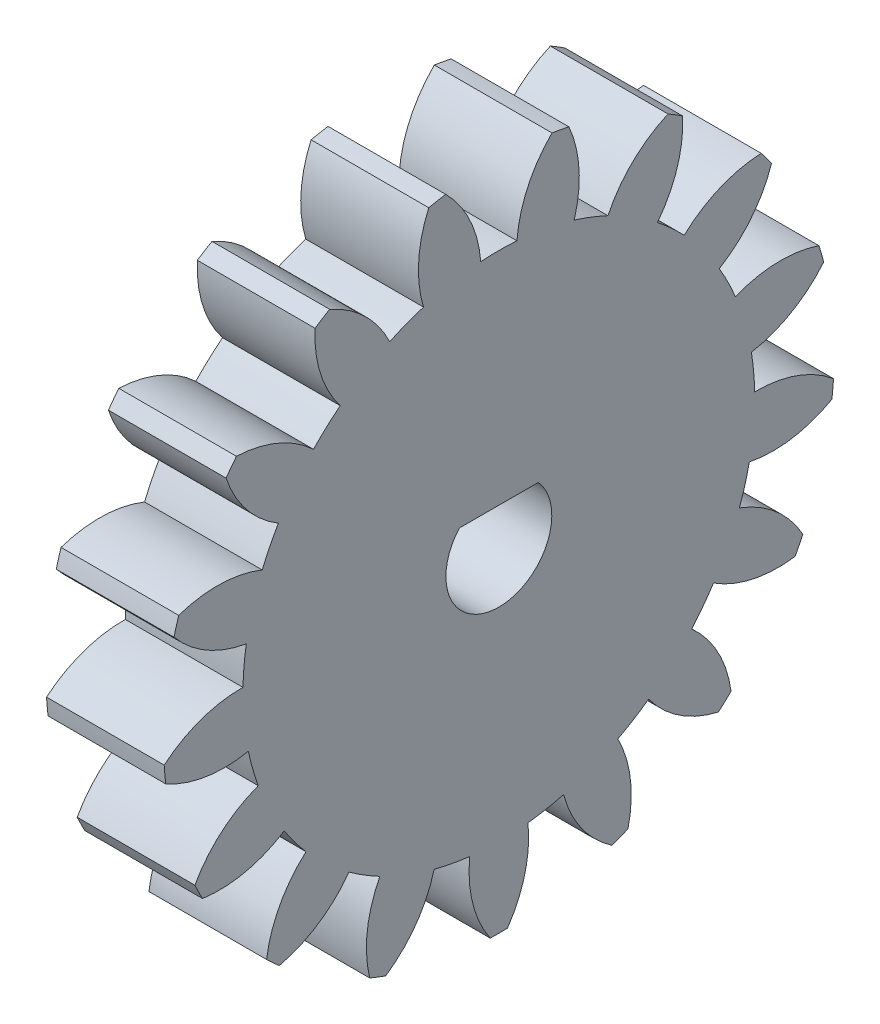
SolidWorks part; units mm, degrees
ref_plane "Plane1" through (0, 0, 0) normal (0, 0, 1) x (1, 0, 0)
ref_plane "Plane2" through (0, 0, 0) normal (0, 1, 0) x (1, 0, 0)
ref_plane "Plane3" through (0, 0, 0) normal (1, 0, 0) x (0, 0, -1)
sketch "HoldingSke" plane through (0, 0, 0) normal (0, 1, 0) x (1, 0, 0)
  line L0 (0, 0) -> (0.6375, -0.1949)
  line L1 (-15, 0) -> (100, 0) construction
  line L2 (0, 0) -> (-2.1039, 2.3779)
  line L3 (0, 0) -> (-11.863, 4.5341)
  line L4 (0, 0) -> (8.2586, 2.5249)
  line L5 (0, 0) -> (-46.8476, -17.4728)
  line L6 (0, 0) -> (-4.1448, -2.7965)
  line L7 (-2.1039, 2.3779) -> (8.6586, 51.2059)
  line L8 (-76.2, 54.61) -> (-76.1, 54.61)
  line L9 (-71.009, 38.7566) -> (-53.1078, 45.2721)
  line L10 (-76.2, 71.12) -> (104.1128, 71.12)
  line L11 (0, 0) -> (-5, 0)
  line L12 (-76.2, 101.6) -> (-76.147, 101.6)
  line L13 (24.9733, 27.94) -> (52.9518, 28.4284)
  line L14 (24.9733, 27.94) -> (24.9743, 27.94)
  line L15 (24.9733, 27.94) -> (100.4006, 29.5858)
  line L16 (-63.627, -1.5) -> (-12.827, -1.5)
  circle A0 centre (0, 0) radius 0.4
  circle A1 centre (0, 0) radius 10.874
  circle A2 centre (0, 0) radius 37.5
  circle A3 centre (0, 0) radius 0.4
  dimension "MHD" = 21.748
  dimension "Hub_dia" = 75
  dimension "Bore" = 0.8
  dimension "MBD" = 0.8
  dimension "Num_teeth" = 17
  dimension "Pitch" = 0.6667
  dimension "Overall_len" = 50
  dimension "Show_teeth" = 17
  dimension "Thickness" = 5
  dimension "OAL" = 50.0001
  dimension "T_dim" = 0.1
  dimension "Ap" = 20
  dimension "H" = 19.05
  dimension "Pitch_radius" = 180.3128
  dimension "Width" = 5
  dimension "Backlash" = 0.053
  dimension "Addendum_fac" = 1
  dimension "Dedendum_fac" = 1.25
  dimension "Clearance_fac" = 0.25
  dimension "Dedendum_add" = 0.001
  dimension "Module" = 1.5
sketch "BasProSke" plane through (0, 0, 0) normal (0, 1, 0) x (1, 0, 0)
  line L0 (-10, 0) -> (60, 0) construction
  line L1 (0, 0) -> (0, 14.25)
  line L2 (0, 0) -> (5, 0)
  line L3 (5, 0) -> (5, 14.25)
  line L4 (5, 14.25) -> (0, 14.25)
  dimension "Thickness" = 5
  dimension "Diameter" = 28.5
revolve "Base-Revolve" add sketch "BasProSke" angle 360 about L0
sketch "TooCutSke" plane through (0, 0, 0) normal (1, 0, 0) x (0, 0, -1)
  line L1 (0, 0) -> (0, 107) construction
  line L2 (0, 0) -> (-1.2691, 12.6867) construction
  line L3 (0, 0) -> (-4.6687, 24.9751) construction
  line L4 (-1.2691, 12.6867) -> (-2.3343, 12.4876) construction
  arc A0 (0.7694, 10.8467) -> (-0.7694, 10.8467) centre (0, 0) ccw
  arc A1 (2.2806, 14.0921) -> (-2.2806, 14.0921) centre (0, 0) ccw
  circle A2 centre (0, 0) radius 12.75 construction
  circle A3 centre (0, 0) radius 11.9811 construction
  arc A4 (-0.7694, 10.8467) -> (-2.2806, 14.0921) centre (-5.8542, 10.4535) ccw
  arc A5 (2.2806, 14.0921) -> (0.7694, 10.8467) centre (5.8542, 10.4535) ccw
  dimension "Root_dia" = 21.748
  dimension "Overcut_dia" = 28.5508
  dimension "Pitch_dia" = 25.5
  dimension "Base_dia" = 23.9622
  dimension "Flank_rad" = 5.1
  dimension "Half_ang" = 10.588
  dimension "Half_CT" = 1.0837
extrude "ToothCut" cut sketch "TooCutSke" along normal through all
fillet "Breaks" [suppressed] radius 0.03
fillet "RootFillets" [suppressed] radius 0.376
pattern_circular "TeethCuts" count 17 every 21.176 about axis through (-10, 0, 0) along (1, 0, 0) of "ToothCut", "RootFillets", "Breaks"
sketch "HubNeaOneSke" plane through (0, 0, 0) normal (-1, 0, 0) x (0, 0, 1)
  circle A0 centre (0, 0) radius 10.874
  dimension "Diameter" = 21.748
extrude "HubNearOne" [suppressed] add sketch "HubNeaOneSke" along normal blind 45.0001
sketch "HubNeaBotSke" plane through (0, 0, 0) normal (-1, 0, 0) x (0, 0, 1)
  circle A0 centre (0, 0) radius 10.874
  dimension "Diameter" = 21.748
extrude "HubNearBoth" [suppressed] add sketch "HubNeaBotSke" along normal blind 22.5
ref_plane "FarPln" through (5, 0, 0) normal (1, 0, 0) x (0, 0, -1)
sketch "HubFarSke" plane through (5, 0, 0) normal (1, 0, 0) x (0, 0, -1)
  circle A0 centre (0, 0) radius 10.874
  dimension "Diameter" = 21.748
extrude "HubFar" [suppressed] add sketch "HubFarSke" along normal blind 22.5
sketch "BorSke" plane through (0, 0, 0) normal (1, 0, 0) x (0, 0, -1)
  circle A0 centre (0, 0) radius 0.4
  dimension "Diameter" = 0.8
extrude "Bore" cut sketch "BorSke" along normal mid plane 100.0001
sketch "KeySke" plane through (0, 0, 0) normal (1, 0, 0) x (0, 0, -1)
  line L0 (-0.05, 0) -> (-0.05, 0.5)
  line L1 (-0.05, 0.5) -> (0.05, 0.5)
  line L2 (0.05, 0.5) -> (0.05, 0)
  line L3 (0, 0) -> (0, 34) construction
  line L4 (-0.05, 0) -> (0.05, 0)
  dimension "Offset" = 0.5
  dimension "Width" = 0.1
extrude "Keyway" [suppressed] cut sketch "KeySke" along normal mid plane 100.0001
pattern_circular "Keyway2" [suppressed] count 2 every 90 about axis through (-10, 0, 0) along (1, 0, 0)
sketch "Sketch1" plane through (5, 0, 0) normal (1, 0, 0) x (0, 0, -1)
  line L0 (-1.6771, 1.5) -> (1.6771, 1.5)
  arc A0 (-1.6771, 1.5) -> (1.6771, 1.5) centre (0, 0) ccw
  dimension "D1" = 2.25
  dimension "D2" = 1.5
extrude "Cut-Extrude1" cut sketch "Sketch1" against normal through all
equation "' \"Module@HoldingSke\" = 6.35"
equation "' \"Num_teeth@HoldingSke\" = 12"
equation "' \"Ap@HoldingSke\" =  20"
equation "' \"Ap@HoldingSke\" = 20"
equation "' \"Width@HoldingSke\" = 0.5 * 25.4"
equation "' \"Hub_dia@HoldingSke\"= 1 * 25.4"
equation "' \"Hub_dia@HoldingSke\" = 1 * 25.4"
equation "' \"Overall_len@HoldingSke\" = 1.0 * 25.4"
equation "' \"Bore@HoldingSke\" = 0.75 * 25.4"
equation "' \"T_dim@HoldingSke\" = 0.1 * 25.4"
equation "' \"Width@KeySke\" = 0.25 * 25.4"
equation "' \"Show_teeth@HoldingSke\" = 13"
equation "' \"Backlash@HoldingSke\" = 0.009 * 25.4"
equation "' \"Addendum_fac@HoldingSke\" = 1.0"
equation "' \"Dedendum_fac@HoldingSke\" = 1.25"
equation "' \"Dedendum_add@HoldingSke\" = 0.00005 * 25.4"
equation "' \"Clearance_fac@HoldingSke\" = 0.25"
equation "\"Pitch@HoldingSke\" = 1 / \"Module@HoldingSke\""
equation "\"Overcut_dia@TooCutSke\" = (\"Num_teeth@HoldingSke\" + 2 * \"Addendum_fac@HoldingSke\") / \"Pitch@HoldingSke\" + 0.002 * 25.4"
equation "\"Pitch_dia@TooCutSke\" = \"Num_teeth@HoldingSke\" / \"Pitch@HoldingSke\""
equation "\"Base_dia@TooCutSke\" = \"Num_teeth@HoldingSke\" / \"Pitch@HoldingSke\" * cos((\"Ap@HoldingSke\"  * 3.14159265 / 180))"
equation "\"Root_dia@TooCutSke\" = (\"Num_teeth@HoldingSke\" + 2) / \"Pitch@HoldingSke\" - 2 * (\"Addendum_fac@HoldingSke\" + \"Dedendum_fac@HoldingSke\") / \"Pitch@HoldingSke\" - \"Dedendum_add@HoldingSke\" * 2"
equation "\"Half_ang@TooCutSke\" = 180 / \"Num_teeth@HoldingSke\""
equation "\"Half_CT@TooCutSke\" = \"Num_teeth@HoldingSke\" / \"Pitch@HoldingSke\" * sin((3.14159265 / 2 / \"Num_teeth@HoldingSke\")) / 2 - 7 * \"Backlash@HoldingSke\" / 4"
equation "\"Flank_rad@TooCutSke\" = \"Num_teeth@HoldingSke\" / \"Pitch@HoldingSke\" / 5"
equation "\"Radius@RootFillets\" = \"Clearance_fac@HoldingSke\" / \"Pitch@HoldingSke\" + \"Dedendum_add@HoldingSke\""
equation "\"Break_rad@Breaks\" = 0.02 / \"Pitch@HoldingSke\""
equation "\"Thickness@HoldingSke\" = \"Width@HoldingSke\""
equation "\"OAL@HoldingSke\" = \"Thickness@HoldingSke\""
equation "\"MHD@HoldingSke\" = (\"Num_teeth@HoldingSke\" + 2) / \"Pitch@HoldingSke\" - 2 * (\"Addendum_fac@HoldingSke\" + \"Dedendum_fac@HoldingSke\")  / \"Pitch@HoldingSke\" - \"Dedendum_add@HoldingSke\" * 2"
equation "\"MBD@HoldingSke\" = (\"Num_teeth@HoldingSke\" + 2) / \"Pitch@HoldingSke\" - 2 * (\"Addendum_fac@HoldingSke\" + \"Dedendum_fac@HoldingSke\")  / \"Pitch@HoldingSke\" - \"Dedendum_add@HoldingSke\" * 2 - 0.002 * 25.4"
equation "\"MHD@HoldingSke\" = ((sgn( \"MHD@HoldingSke\" - \"Hub_dia@HoldingSke\" )-1)*( \"MHD@HoldingSke\" - \"Hub_dia@HoldingSke\" ))/-2+ \"Hub_dia@HoldingSke\""
equation "\"MBD@HoldingSke\" = ((sgn( \"MBD@HoldingSke\" - \"Bore@HoldingSke\" )-1)*( \"MBD@HoldingSke\" - \"Bore@HoldingSke\" ))/-2+ \"Bore@HoldingSke\""
equation "\"OAL@HoldingSke\" = ((sgn( \"OAL@HoldingSke\" - \"Overall_len@HoldingSke\" )+1)*( \"OAL@HoldingSke\" - \"Overall_len@HoldingSke\" ))/2 + \"Overall_len@HoldingSke\" + 0.000002 * 25.4"
equation "\"Num_teeth@TeethCuts\" = int( \"Show_teeth@HoldingSke\" ) + 1"
equation "\"Num_teeth@TeethCuts\" = ((sgn( \"Num_teeth@TeethCuts\" - \"Num_teeth@HoldingSke\" )-1)*( \"Num_teeth@TeethCuts\" - \"Num_teeth@HoldingSke\" ))/-2+ \"Num_teeth@HoldingSke\""
equation "\"Num_teeth@TeethCuts\" = ((sgn( \"Num_teeth@TeethCuts\" - 2.0)+1)*( \"Num_teeth@TeethCuts\" - 2.0))/2 +2.0"
equation "\"Angle@TeethCuts\" = 360.0 / \"Num_teeth@HoldingSke\""
equation "\"Diameter@BasProSke\" = (\"Num_teeth@HoldingSke\" + 2 * \"Addendum_fac@HoldingSke\") / \"Pitch@HoldingSke\""
equation "\"Thickness@BasProSke\"  = \"Thickness@HoldingSke\""
equation "' \"Fillet_rad@BasProSke\" =  \"Thickness@HoldingSke\" * 0.05"
equation "' \"Fillet_rad@BasProSke\" = \"Thickness@HoldingSke\" * 0.05"
equation "\"MHD@HoldingSke\" = ((sgn( \"MHD@HoldingSke\" - \"Root_dia@TooCutSke\" )-1)*( \"MHD@HoldingSke\" - \"Root_dia@TooCutSke\" ))/-2+ \"Root_dia@TooCutSke\""
equation "\"Diameter@HubNeaOneSke\" = \"MHD@HoldingSke\""
equation "\"Length@HubNearOne\" = \"OAL@HoldingSke\" - \"Thickness@BasProSke\""
equation "\"Diameter@HubNeaBotSke\" = \"MHD@HoldingSke\""
equation "\"Length@HubNearBoth\" = ( \"OAL@HoldingSke\" - \"Thickness@BasProSke\" ) / 2.0"
equation "\"Thickness@FarPln\" = \"Thickness@BasProSke\""
equation "\"Diameter@HubFarSke\" = \"MHD@HoldingSke\""
equation "\"Length@HubFar\" = ( \"OAL@HoldingSke\" - \"Thickness@BasProSke\" ) / 2.0"
equation "\"Diameter@BorSke\" = \"MBD@HoldingSke\""
equation "\"D1@Bore\" = \"OAL@HoldingSke\" * 2.0"
equation "\"D1@Keyway\" = \"OAL@HoldingSke\" * 2.0"
equation "\"Offset@KeySke\" = \"T_dim@HoldingSke\" + \"MBD@HoldingSke\" / 2.0"
